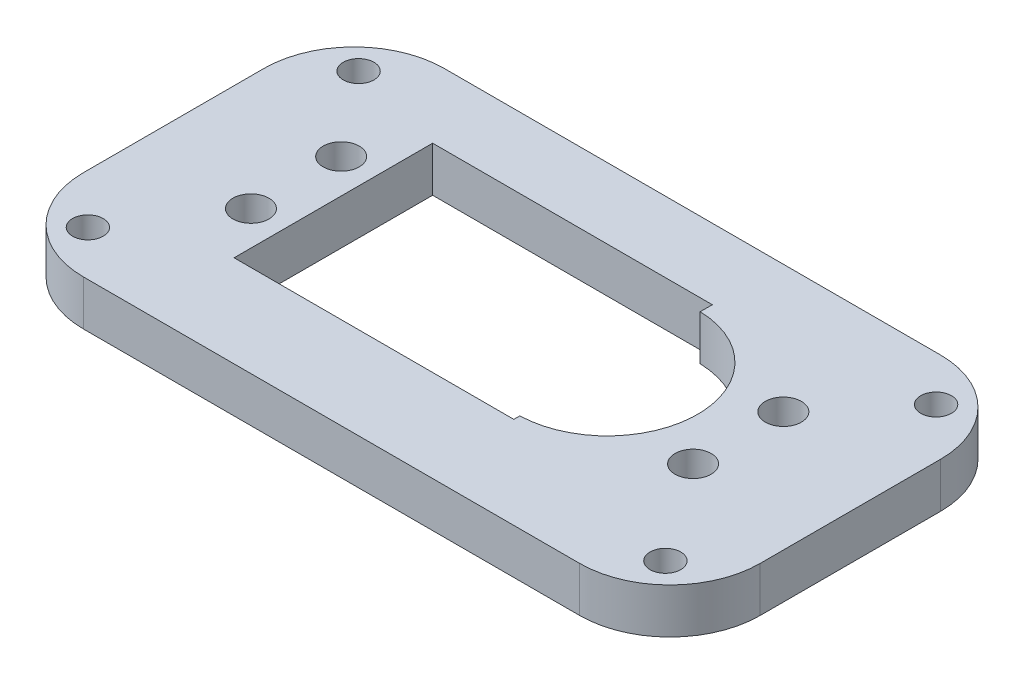
SolidWorks part; units mm, degrees
ref_plane "Front Plane" through (0, 0, 0) normal (0, 0, 1) x (1, 0, 0)
ref_plane "Top Plane" through (0, 0, 0) normal (0, 1, 0) x (1, 0, 0)
ref_plane "Right Plane" through (0, 0, 0) normal (1, 0, 0) x (0, 0, -1)
sketch "Sketch9" plane through (0, 0, 0) normal (0, 1, 0) x (1, 0, 0)
  line L1 (-37.5, 20) -> (37.5, 20)
  line L2 (-37.5, 20) -> (-37.5, -20)
  line L3 (-37.5, -20) -> (37.5, -20)
  line L4 (37.5, 20) -> (37.5, -20)
  line L5 (-37.5, 20) -> (37.5, -20) construction
  line L6 (-37.5, -20) -> (37.5, 20) construction
  point P0 (0, 0)
  point P5 (25.2979, 6.6904)
  dimension "D1" = 75
  dimension "D2" = 40
extrude "Boss-Extrude5" add sketch "Sketch9" along normal blind 5 separate body
sketch "Sketch10" plane through (0, 5, 0) normal (0, 1, 0) x (1, 0, 0)
  line L4 (-20.9778, 12.1848) -> (-20.9811, -9.8172)
  line L5 (-20.9811, -9.8172) -> (10.0222, -9.8219)
  line L6 (10.0222, -9.8219) -> (10.0222, 12.1781)
  line L7 (10.0222, 12.1781) -> (-20.9778, 12.1848)
  circle A0 centre (24.2299, 5.8391) radius 2
  circle A1 centre (24.2299, -4.1609) radius 2
  circle A2 centre (-24.7701, 5.8391) radius 2
  circle A3 centre (-24.7701, -4.1609) radius 2
  circle A4 centre (9.7299, 0.8391) radius 10
  circle A5 centre (-3.2701, 0.8391) radius 8
  point P20 (0, 0)
  dimension "D1" = 16
extrude "Cut-Extrude5" cut sketch "Sketch10" against normal through all contours A5 A4 L6 L7 L4 L5 | L6 A4 | A5 A4 L6 | A4 A5 | A4 A5 | A0 | A1 | A2 | A3
sketch "Sketch11" plane through (0, 5, 0) normal (0, 1, 0) x (1, 0, 0)
  circle A0 centre (-32, 15) radius 1.7
  circle A1 centre (32, 15) radius 1.7
  circle A2 centre (32, -15) radius 1.7
  circle A3 centre (-32, -15) radius 1.7
  dimension "D1" = 3.4
  dimension "D3" = 64
  dimension "D5" = 30
  dimension "D2" = 32
  dimension "D4" = 15
extrude "Cut-Extrude6" cut sketch "Sketch11" against normal through all
fillet "Fillet1" radius 10 4 edges at (37.5, 2.5, 20) (-37.5, 2.5, 20) (-37.5, 2.5, -20) (37.5, 2.5, -20)
